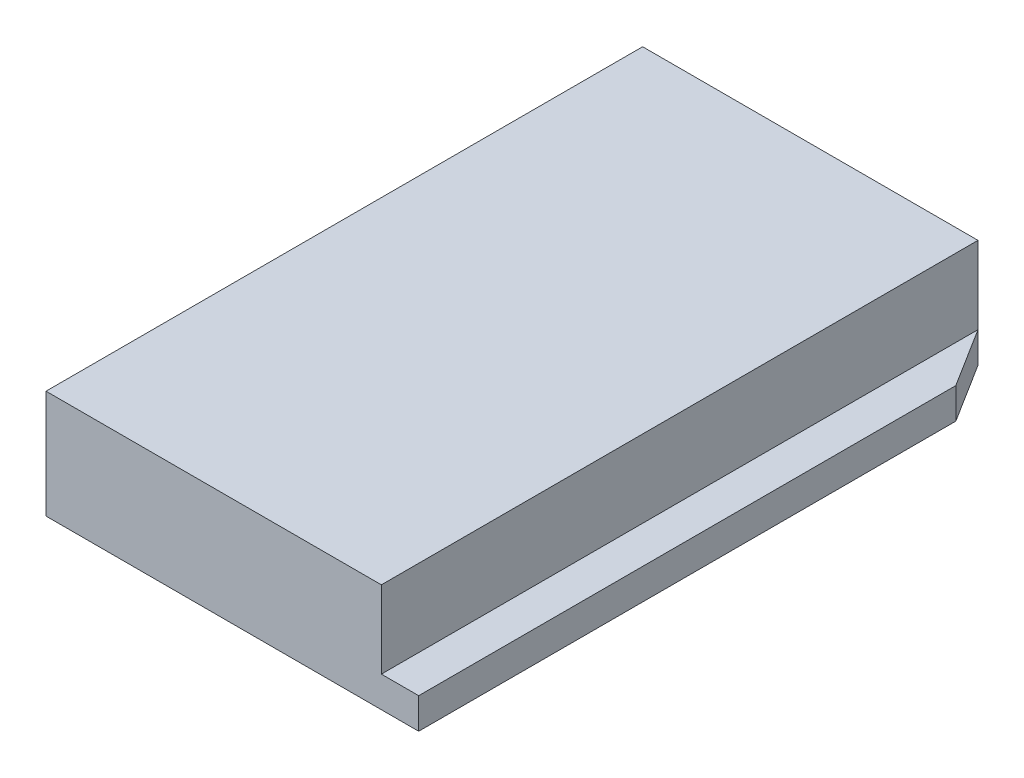
SolidWorks part; units mm, degrees
ref_plane "Front Plane" through (0, 0, 0) normal (0, 0, 1) x (1, 0, 0)
ref_plane "Top Plane" through (0, 0, 0) normal (0, 1, 0) x (1, 0, 0)
ref_plane "Right Plane" through (0, 0, 0) normal (1, 0, 0) x (0, 0, -1)
sketch "Sketch1" plane through (0, 0, 0) normal (0, 1, 0) x (1, 0, 0)
  line L1 (0, 0) -> (7.874, 0)
  line L2 (0, 0) -> (0, 14.0081)
  line L3 (0, 14.0081) -> (7.874, 14.0081)
  line L4 (7.874, 0) -> (7.874, 14.0081)
  dimension "D1" = 7.874
  dimension "D2" = 14.0081
extrude "Boss-Extrude1" add sketch "Sketch1" along normal blind 2.54
sketch "Sketch2" plane through (0, 0, -14.0081) normal (0, 0, -1) x (-1, 0, 0)
  line L0 (-7.874, 2.54) -> (0, 2.54) construction
  line L1 (-7.0485, 1.8669) -> (-5.9468, 1.8669)
  line L2 (-7.0485, 1.8669) -> (-7.0485, 0.8636)
  line L3 (-7.0485, 0.8636) -> (-5.9468, 0.8636)
  line L4 (-5.9468, 1.8669) -> (-5.9468, 0.8636)
  line L5 (-4.5228, 1.8669) -> (-3.4211, 1.8669)
  line L6 (-4.5228, 1.8669) -> (-4.5228, 0.8636)
  line L7 (-4.5228, 0.8636) -> (-3.4211, 0.8636)
  line L8 (-3.4211, 1.8669) -> (-3.4211, 0.8636)
  line L9 (-1.9971, 0.8636) -> (-0.8953, 0.8636)
  line L10 (-1.9971, 0.8636) -> (-1.9971, 1.8669)
  line L11 (-1.9971, 1.8669) -> (-0.8953, 1.8669)
  line L12 (-0.8953, 0.8636) -> (-0.8953, 1.8669)
  line L13 (-7.874, 0) -> (0, 0) construction
  line L14 (-7.874, 2.54) -> (-7.874, 0) construction
  line L15 (0, 2.54) -> (0, 0) construction
  line L16 (-5.9468, 1.8638) -> (-4.5228, 1.8638) construction
  line L18 (-3.4211, 1.8638) -> (-1.9971, 1.8638) construction
  dimension "D1" = 0.6731
  dimension "D2" = 0.8636
  dimension "D3" = 0.8255
  dimension "D4" = 0.8953
  dimension "D5" = 3.9497
extrude "Cut-Extrude1" cut sketch "Sketch2" against normal blind 8.636
sketch "Sketch3" plane through (0, 2.54, 0) normal (0, 1, 0) x (1, 0, 0)
  line L1 (0, 0) -> (7.874, 0)
  line L2 (0, 0) -> (0, 4.8895)
  line L3 (0, 4.8895) -> (7.874, 4.8895)
  line L4 (7.874, 0) -> (7.874, 4.8895)
  line L5 (7.874, 0) -> (7.874, 14.0081) construction
  dimension "D1" = 4.8895
extrude "Boss-Extrude2" [suppressed] add sketch "Sketch3" along normal blind 0.2032
sketch "Sketch5" plane through (0, 0, 0) normal (0, -1, 0) x (1, 0, 0)
  line L0 (0, -14.0081) -> (0, 0) construction
  line L2 (7.874, -14.0081) -> (7.874, 0)
  line L3 (7.874, 0) -> (8.7503, 0)
  line L4 (8.7503, -12.6111) -> (8.7503, 0)
  line L5 (7.874, -14.0081) -> (8.7503, -12.6111)
  dimension "D1" = 8.7503
  dimension "D2" = 1.397
extrude "Boss-Extrude3" add sketch "Sketch5" against normal blind 0.7239
